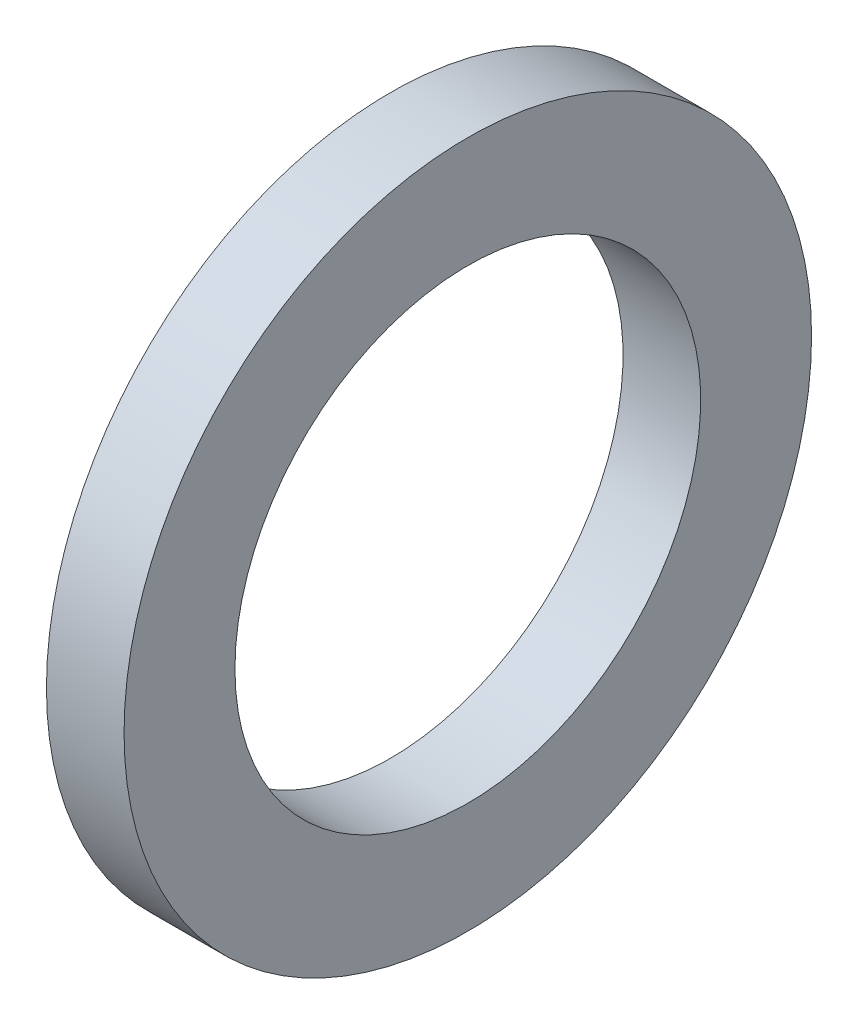
SolidWorks part; units mm, degrees
ref_plane "Plane1" through (0, 0, 0) normal (0, 0, 1) x (1, 0, 0)
ref_plane "Plane2" through (0, 0, 0) normal (0, 1, 0) x (1, 0, 0)
ref_plane "Plane3" through (0, 0, 0) normal (1, 0, 0) x (0, 0, -1)
sketch "Sketch1" plane through (0, 0, 0) normal (0, 0, 1) x (1, 0, 0)
  line L0 (-34.925, 0) -> (9.525, 0) construction
  line L1 (0, 10.5) -> (0, 15.5)
  line L2 (0, 15.5) -> (-3.5, 15.5)
  line L3 (-3.5, 15.5) -> (-3.5, 10.5)
  line L4 (-3.5, 10.5) -> (0, 10.5)
  dimension "Thickness" = 3.5
  dimension "Inside_dia" = 21
  dimension "Outside_dia" = 31
revolve "Base-Revolve" add sketch "Sketch1" angle 360 about L0
